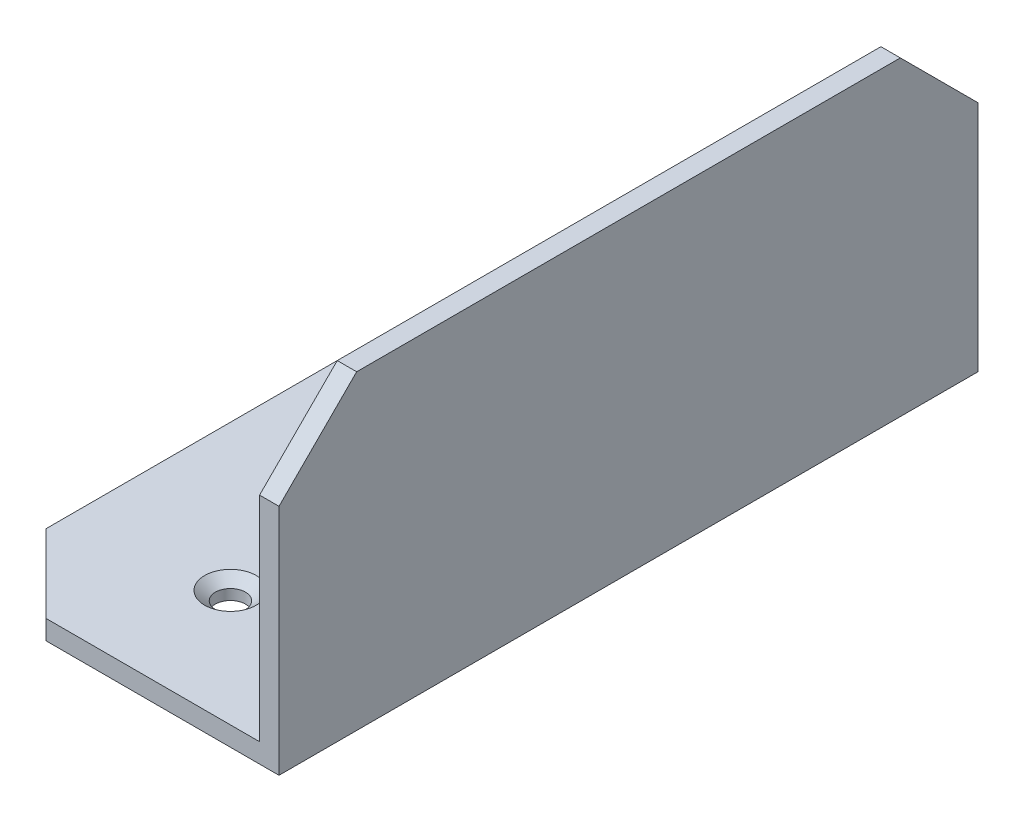
SolidWorks part; units mm, degrees
material "6063-T5"
ref_plane "Front Plane" through (0, 0, 0) normal (0, 0, 1) x (1, 0, 0)
ref_plane "Top Plane" through (0, 0, 0) normal (0, 1, 0) x (1, 0, 0)
ref_plane "Right Plane" through (0, 0, 0) normal (1, 0, 0) x (0, 0, -1)
sketch "Sketch2" plane through (0, 0, 0) normal (0, 0, 1) x (1, 0, 0)
  line L0 (0, 0) -> (0, 50.8)
  line L1 (0, 0) -> (-50.8, 0)
  line L2 (-3.175, 3.175) -> (-3.175, 50.8)
  line L3 (-3.175, 3.175) -> (-50.8, 3.175)
  line L4 (0, 50.8) -> (-3.175, 50.8)
  line L5 (-50.8, 0) -> (-50.8, 3.175)
  dimension "D1" = 50.8
  dimension "D2" = 50.8
  dimension "D3" = 3.175
extrude "Boss-Extrude1" add sketch "Sketch2" against normal blind 114.3
chamfer "Chamfer1" distance 12.7 angle 45 4 edges at (-50.8, 1.5875, -114.3) (-1.5875, 50.8, -114.3) (-1.5875, 50.8, 0) (-50.8, 1.5875, 0)
hole_wizard "CSK for #8 Flat Head Machine Screw (100)1" positions "Sketch3" profile "Sketch4" countersink size "#8" standard "ANSI Inch" end condition through all
sketch "Sketch3" plane through (0, 3.175, 0) normal (0, 1, 0) x (1, 0, 0)
  line L0 (-50.8, 57.15) -> (-3.175, 57.15) construction
  line L1 (-50.8, 101.6) -> (-50.8, 12.7) construction
  line L2 (-3.175, 114.3) -> (-3.175, 0) construction
  line L4 (-26.9875, 57.15) -> (-26.9875, 0) construction
  line L5 (-3.175, 0) -> (-38.1, 0) construction
  point P26 (-26.9875, 19.05)
  point P27 (-26.9875, 57.15)
  point P29 (-26.9875, 139.7)
  point P33 (0, 0)
  point P34 (-26.9875, 26.3792)
  point P35 (0, 0)
  point P36 (0, 0)
  point P37 (-26.9875, 95.25)
  dimension "D1" = 38.1
sketch "Sketch4" plane through (-26.9875, 3.175, -95.25) normal (1, 0, 0) x (0, 0, 1)
  line L0 (0, 0) -> (0, 3.175)
  line L1 (0, 3.175) -> (2.4574, 3.175)
  line L2 (2.4574, 3.175) -> (2.4574, 1.4759)
  line L3 (2.4574, 1.4759) -> (4.2164, 0)
  line L5 (4.2164, 0) -> (0, 0)
  line L6 (-2.4574, 1.4759) -> (-4.2164, 0) construction
  line L11 (0, -6.35) -> (0, 107.95) construction
  dimension "Thru Hole Dia." = 4.9149
  dimension "Thru Hole Depth" = 3.175
  dimension "Near C'Sink Dia." = 8.4328
  dimension "Near C'Sink Angle" = 100
equation "\"D2@Sketch2\"=\"D1@Sketch2\""
